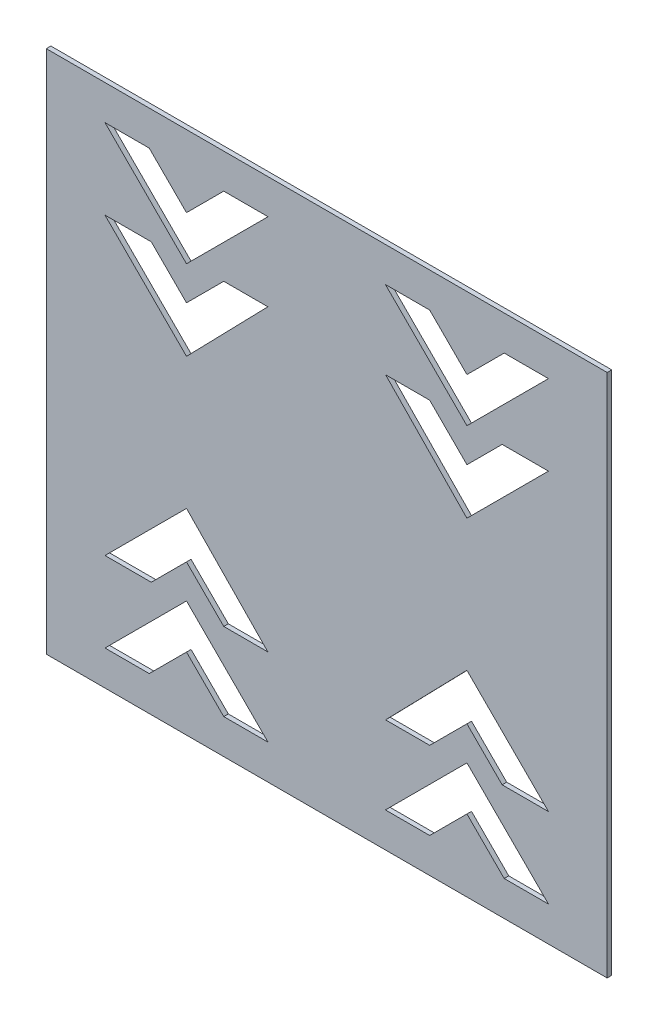
SolidWorks part; units mm, degrees
ref_plane "前视基准面" through (0, 0, 0) normal (0, 0, 1) x (1, 0, 0)
ref_plane "上视基准面" through (0, 0, 0) normal (0, 1, 0) x (1, 0, 0)
ref_plane "右视基准面" through (0, 0, 0) normal (1, 0, 0) x (0, 0, -1)
sketch "草图1" plane through (0, 0, 0) normal (0, 0, 1) x (1, 0, 0)
  line L1 (-123, 115) -> (123, 115)
  line L2 (-123, 115) -> (-123, -115)
  line L3 (-123, -115) -> (123, -115)
  line L4 (123, 115) -> (123, -115)
  line L5 (-123, 115) -> (123, -115) construction
  line L6 (-123, -115) -> (123, 115) construction
  point P0 (0, 0)
  dimension "D1" = 246
  dimension "D2" = 230
extrude "凸台-拉伸1" add sketch "草图1" along normal blind 2
sketch "草图2" plane through (0, 0, 2) normal (0, 0, 1) x (1, 0, 0)
  line L0 (0, -1000) -> (0, 49000) construction
  line L1 (-61.5, -1002.6923) -> (-61.5, 48997.3077) construction
  line L2 (-61.5, -66.1538) -> (-93.6346, -98.2885) construction
  line L3 (-61.5, -66.1538) -> (-29.3654, -98.2885) construction
  line L4 (-93.6346, -98.2885) -> (-78.4615, -98.2885) construction
  line L5 (-78.4615, -98.2885) -> (-61.5, -81.3269) construction
  line L6 (-61.5, -81.3269) -> (-44.5385, -98.2885) construction
  line L7 (-44.5385, -98.2885) -> (-29.3654, -98.2885) construction
  line L8 (-61.5, -31.0167) -> (-93.6346, -63.1513) construction
  line L9 (-93.6346, -63.1513) -> (-77.5673, -63.1513) construction
  line L10 (-77.5673, -63.1513) -> (-61.5, -47.084) construction
  line L11 (-61.5, -47.084) -> (-44.5385, -64.0456) construction
  line L12 (-44.5385, -64.0456) -> (-29.3654, -64.0456) construction
  line L13 (-61.5, -31.0167) -> (-29.3654, -64.0456) construction
  line L14 (-61.4853, -28.8808) -> (-97.2559, -64.6513)
  line L15 (-97.2559, -64.6513) -> (-76.946, -64.6513)
  line L16 (-76.946, -64.6513) -> (-61.5, -49.2054)
  line L17 (-61.5, -49.2054) -> (-45.1598, -65.5456)
  line L18 (-45.1598, -65.5456) -> (-25.8132, -65.5456)
  line L19 (-61.4853, -28.8808) -> (-25.8132, -65.5456)
  line L20 (-61.5147, -33.1527) -> (-90.0133, -61.6513)
  line L21 (-90.0133, -61.6513) -> (-78.1886, -61.6513)
  line L22 (-78.1886, -61.6513) -> (-61.5, -44.9627)
  line L23 (-61.5, -44.9627) -> (-43.9171, -62.5456)
  line L24 (-43.9171, -62.5456) -> (-32.9176, -62.5456)
  line L25 (-61.5147, -33.1527) -> (-32.9176, -62.5456)
  line L26 (-61.5, -64.0325) -> (-97.2559, -99.7885)
  line L27 (-97.2559, -99.7885) -> (-77.8402, -99.7885)
  line L28 (-77.8402, -99.7885) -> (-61.5, -83.4482)
  line L29 (-61.5, -83.4482) -> (-45.1598, -99.7885)
  line L30 (-45.1598, -99.7885) -> (-25.7441, -99.7885)
  line L31 (-61.5, -64.0325) -> (-25.7441, -99.7885)
  line L32 (-61.5, -68.2752) -> (-90.0133, -96.7885)
  line L33 (-90.0133, -96.7885) -> (-79.0829, -96.7885)
  line L34 (-79.0829, -96.7885) -> (-61.5, -79.2056)
  line L35 (-61.5, -79.2056) -> (-43.9171, -96.7885)
  line L36 (-43.9171, -96.7885) -> (-32.9867, -96.7885)
  line L37 (-61.5, -68.2752) -> (-32.9867, -96.7885)
  dimension "D1" = 61.5
  dimension "D2" = 1.5
  dimension "D3" = 1.5
  dimension "D4" = 1.5
  dimension "D5" = 1.5
extrude "切除-拉伸2" cut sketch "草图2" against normal through all
mirror "镜向1" about plane through (0, 0, 0) normal (0, 1, 0) of "切除-拉伸2"
mirror "镜向2" about plane through (0, 0, 0) normal (1, 0, 0) of "镜向1", "切除-拉伸2"
